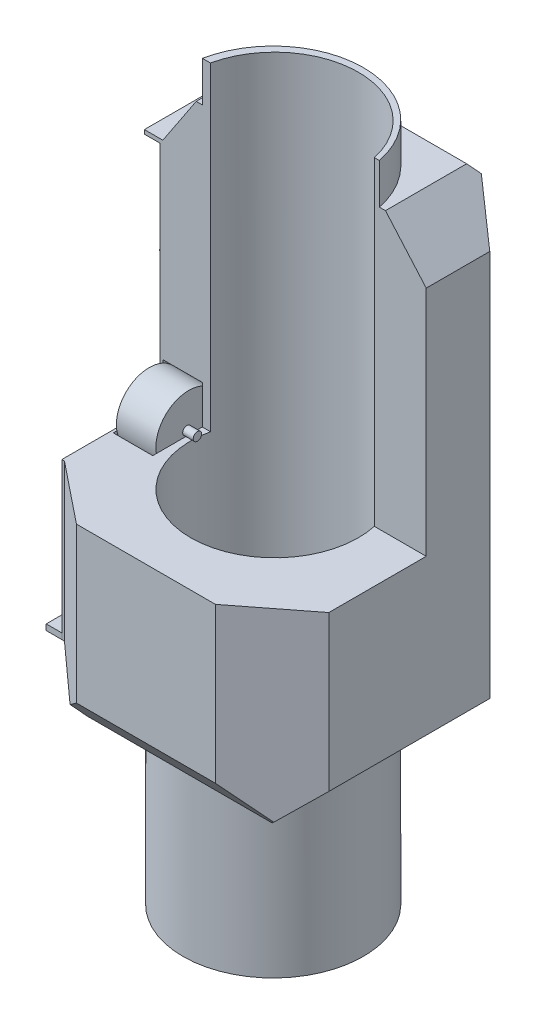
SolidWorks part; units mm, degrees
ref_plane "Front Plane" through (0, 0, 0) normal (0, 0, 1) x (1, 0, 0)
ref_plane "Top Plane" through (0, 0, 0) normal (0, 1, 0) x (1, 0, 0)
ref_plane "Right Plane" through (0, 0, 0) normal (1, 0, 0) x (0, 0, -1)
sketch "Sketch1" plane through (0, 0, 0) normal (0, 1, 0) x (1, 0, 0)
  line L1 (0, 0) -> (-100, 0)
  line L2 (0, 0) -> (0, 100)
  line L3 (0, 100) -> (-100, 100)
  line L4 (-100, 0) -> (-100, 100)
  dimension "D1" = 100
  dimension "D2" = 100
extrude "Boss-Extrude1" add sketch "Sketch1" along normal blind 180
sketch "Sketch2" plane through (0, 180, 0) normal (0, 1, 0) x (1, 0, 0)
  circle A0 centre (-51.3773, 49.0765) radius 34.2578
  point P2 (-49.1037, 52.2166)
  point P3 (-48.8771, 51.8469)
  point P4 (-51.3773, 49.0765)
extrude "Boss-Extrude2" add sketch "Sketch2" along normal mid plane 700
sketch "Sketch3" plane through (0, 0, 0) normal (1, 0, 0) x (0, 0, -1)
  line L1 (-18.5833, 361.0481) -> (133.4231, 361.0481)
  line L2 (-18.5833, 361.0481) -> (-18.5833, 643.5005)
  line L3 (-18.5833, 643.5005) -> (133.4231, 643.5005)
  line L4 (133.4231, 361.0481) -> (133.4231, 643.5005)
extrude "Cut-Extrude2" cut sketch "Sketch3" against normal blind 400
sketch "Sketch4" plane through (0, 0, 0) normal (1, 0, 0) x (0, 0, -1)
  line L0 (12.982, 0) -> (-8.9942, 25.8281)
  line L1 (-8.9942, 25.8281) -> (-18.5645, -15.2595)
  line L2 (-18.5645, -15.2595) -> (12.982, 0)
  line L3 (85.0725, -1.4481) -> (109.2376, 19.1131)
  line L4 (109.2376, 19.1131) -> (115.92, -3.2674)
  line L5 (115.92, -3.2674) -> (85.0725, -1.4481)
  line L6 (12.982, 180) -> (-8.9942, 148.5376)
  line L7 (-8.9942, 148.5376) -> (-15.4182, 193.2193)
  line L8 (-15.4182, 193.2193) -> (12.982, 180)
  line L9 (85.0725, 181.8543) -> (103.8412, 159.7959)
  line L10 (103.8412, 159.7959) -> (106.1325, 198.6474)
  line L11 (106.1325, 198.6474) -> (85.0725, 181.8543)
extrude "Cut-Extrude3" cut sketch "Sketch4" against normal blind 400
sketch "Sketch5" plane through (0, 0, 0) normal (0, 0, 1) x (1, 0, 0)
  line L0 (-85.6233, 0) -> (-106.3704, 21.4264)
  line L1 (-106.3704, 21.4264) -> (-122.2889, 3.2093)
  line L2 (-122.2889, 3.2093) -> (-93.5263, -19.8847)
  line L3 (-93.5263, -19.8847) -> (-85.6233, 0)
  line L4 (-15.695, 0) -> (0, 15.2574)
  line L5 (0, 15.2574) -> (12.1227, 15.2574)
  line L6 (12.1227, 15.2574) -> (10.5631, -19.8847)
  line L7 (10.5631, -19.8847) -> (-15.695, 0)
  line L8 (-87.1665, 180.2481) -> (-106.3704, 151.2911)
  line L9 (-106.3704, 151.2911) -> (-117.7055, 200.5011)
  line L10 (-117.7055, 200.5011) -> (-87.1665, 180.2481)
  line L11 (-15.695, 180.2481) -> (7.8338, 153.2796)
  line L12 (7.8338, 153.2796) -> (0, 193.9412)
  line L13 (0, 193.9412) -> (-15.695, 180.2481)
extrude "Cut-Extrude4" cut sketch "Sketch5" against normal blind 400
sketch "Sketch6" plane through (0, 180, 0) normal (0, 1, 0) x (1, 0, 0)
  line L1 (-112.387, 28.4004) -> (-64.2613, -10.2128)
  line L2 (-112.387, 28.4004) -> (-124.6497, -15.5119)
  line L3 (-124.6497, -15.5119) -> (-84.4064, -15.5119)
  line L4 (-64.2613, -10.2128) -> (-84.4064, -15.5119)
  line L5 (-97.0655, 135.8618) -> (-119.3755, 77.7927)
  line L6 (-97.0655, 135.8618) -> (-66.4287, 110.5752)
  line L7 (-66.4287, 110.5752) -> (-118.0433, 64.3476)
  line L8 (-119.3755, 77.7927) -> (-118.0433, 64.3476)
  line L9 (-24.6964, -21.8158) -> (11.0921, -8.9736)
  line L10 (-24.6964, -21.8158) -> (-38.5316, -11.1392)
  line L11 (-38.5316, -11.1392) -> (17.4283, 32.3938)
  line L12 (11.0921, -8.9736) -> (17.4283, 32.3938)
  line L13 (-17.4455, 140.8044) -> (35.4175, 107.2625)
  line L14 (-17.4455, 140.8044) -> (-31.7244, 103.6253)
  line L15 (-31.7244, 103.6253) -> (9.3055, 72.9964)
  line L16 (35.4175, 107.2625) -> (9.3055, 72.9964)
  point P4 (-17.4455, 140.8044)
  point P5 (-30.2763, 114.984)
  point P6 (35.4175, 107.2625)
  point P19 (-30.6265, 106.484)
  point P20 (-11.2095, 88.3109)
extrude "Cut-Extrude5" cut sketch "Sketch6" against normal blind 400
sketch "Sketch7" plane through (0, 0, 0) normal (0, 0, 1) x (1, 0, 0)
  line L1 (-146.2029, -210.0437) -> (13.9564, -210.0437)
  line L2 (-146.2029, -210.0437) -> (-146.2029, -62.6814)
  line L3 (-146.2029, -62.6814) -> (13.9564, -62.6814)
  line L4 (13.9564, -210.0437) -> (13.9564, -62.6814)
extrude "Cut-Extrude6" cut sketch "Sketch7" against normal blind 400
sketch "Sketch8" plane through (0, 0, 0) normal (0, 0, 1) x (1, 0, 0)
  line L1 (-127.1965, 251.4288) -> (20.1142, 251.4288)
  line L2 (-127.1965, 251.4288) -> (-127.1965, 413.4677)
  line L3 (-127.1965, 413.4677) -> (20.1142, 413.4677)
  line L4 (20.1142, 251.4288) -> (20.1142, 413.4677)
extrude "Cut-Extrude7" cut sketch "Sketch8" against normal blind 400
sketch "Sketch9" plane through (0, 251.4288, 0) normal (0, 1, 0) x (1, 0, 0)
  circle A0 centre (-50.809, 49.032) radius 31.8473
  point P2 (-50.6049, 49.6989)
  point P3 (-51.6378, 48.9774)
  point P4 (-50.809, 49.032)
extrude "Cut-Extrude8" cut sketch "Sketch9" against normal blind 400
sketch "Sketch10" plane through (-100, 0, 0) normal (-1, 0, 0) x (0, 0, 1)
  line L1 (-55.8114, 74.0839) -> (84.4096, 74.0839)
  line L2 (-55.8114, 74.0839) -> (-55.8114, 286.1174)
  line L3 (-55.8114, 286.1174) -> (84.4096, 286.1174)
  line L4 (84.4096, 74.0839) -> (84.4096, 286.1174)
extrude "Cut-Extrude9" cut sketch "Sketch10" against normal blind 400
sketch "Sketch11" plane through (-100, 0, 0) normal (-1, 0, 0) x (0, 0, 1)
  circle A0 centre (-50.4133, 76.2646) radius 13.6031
  point P2 (-50.4133, 76.2646)
extrude "Cut-Extrude11" cut sketch "Sketch11" against normal blind 15
sketch "Sketch12" plane through (-85, 0, 0) normal (-1, 0, 0) x (0, 0, 1)
  circle A0 centre (-50.6588, 76.2225) radius 12.4954
  point P2 (-51.6147, 75.8831)
  point P3 (-50.6588, 76.2225)
extrude "Boss-Extrude3" add sketch "Sketch12" along normal blind 15
sketch "Sketch13" plane through (-85, 0, 0) normal (1, 0, 0) x (0, 0, -1)
  circle A0 centre (49.9452, 75.9448) radius 1.5949
extrude "Boss-Extrude4" add sketch "Sketch13" along normal blind 4
sketch "Sketch14" plane through (-100, 0, 0) normal (-1, 0, 0) x (0, 0, 1)
  line L1 (-115.7243, 195.3259) -> (-14.9757, 195.3259)
  line L2 (-115.7243, 195.3259) -> (-115.7243, 305.8809)
  line L3 (-115.7243, 305.8809) -> (-14.9757, 305.8809)
  line L4 (-14.9757, 195.3259) -> (-14.9757, 305.8809)
extrude "Cut-Extrude13" cut sketch "Sketch14" against normal blind 400
sketch "Sketch15" plane through (-100, 0, 0) normal (-1, 0, 0) x (0, 0, 1)
  line L0 (-18.4618, 14.8474) -> (-80.5077, 14.8474)
  line L1 (-80.5077, 14.8474) -> (-80.5077, 160.8968)
  line L2 (-80.5077, 160.8968) -> (-55.8114, 160.8968)
  line L3 (-55.8114, 160.8968) -> (-55.8114, 74.0839)
  line L4 (-55.8114, 74.0839) -> (-18.4618, 74.0839)
  line L5 (-18.4618, 74.0839) -> (-18.4618, 14.8474)
extrude "Boss-Extrude5" add sketch "Sketch15" along normal blind 1
sketch "Sketch16" plane through (-101, 0, 0) normal (-1, 0, 0) x (0, 0, 1)
  line L1 (-51.5273, 29.9073) -> (-27.023, 29.9073)
  line L2 (-51.5273, 29.9073) -> (-51.5273, 60.3656)
  line L3 (-51.5273, 60.3656) -> (-27.023, 60.3656)
  line L4 (-27.023, 29.9073) -> (-27.023, 60.3656)
extrude "Boss-Extrude6" add sketch "Sketch16" along normal blind 5
sketch "Sketch17" plane through (-101, 0, 0) normal (-1, 0, 0) x (0, 0, 1)
  line L1 (-76.3814, 119.2079) -> (-57.7119, 119.2079)
  line L2 (-76.3814, 119.2079) -> (-76.3814, 141.6106)
  line L3 (-76.3814, 141.6106) -> (-57.7119, 141.6106)
  line L4 (-57.7119, 119.2079) -> (-57.7119, 141.6106)
extrude "Boss-Extrude7" add sketch "Sketch17" along normal blind 1
sketch "Sketch18" plane through (-102, 0, 0) normal (-1, 0, 0) x (0, 0, 1)
  line L1 (-74.0789, 127.628) -> (-69.1713, 127.628)
  line L2 (-74.0789, 127.628) -> (-74.0789, 132.7988)
  line L3 (-74.0789, 132.7988) -> (-69.1713, 132.7988)
  line L4 (-69.1713, 127.628) -> (-69.1713, 132.7988)
  line L5 (-60.3069, 127.1415) -> (-64.2884, 127.1415)
  line L6 (-60.3069, 127.1415) -> (-60.3069, 132.5929)
  line L7 (-60.3069, 132.5929) -> (-64.2884, 132.5929)
  line L8 (-64.2884, 127.1415) -> (-64.2884, 132.5929)
extrude "Boss-Extrude8" add sketch "Sketch18" along normal blind 1
sketch "Sketch19" plane through (-102, 0, 0) normal (-1, 0, 0) x (0, 0, 1)
  line L0 (-66.9765, 134.8688) -> (-73.7929, 134.8688)
  line L1 (-73.7929, 134.8688) -> (-73.7929, 134.1083)
  line L2 (-73.7929, 134.1083) -> (-74.5719, 134.1083)
  line L3 (-74.5719, 134.1083) -> (-74.5719, 140.5127)
  line L4 (-74.5719, 140.5127) -> (-73.7929, 140.5127)
  line L5 (-73.7929, 140.5127) -> (-72.166, 140.5127)
  line L6 (-66.9765, 134.8688) -> (-66.9765, 135.4972)
  line L7 (-66.9765, 135.4972) -> (-73.7929, 135.4233)
  line L8 (-73.7929, 135.4233) -> (-73.7929, 139.5456)
  line L9 (-73.7929, 139.5456) -> (-72.9212, 139.5456)
  line L10 (-72.9212, 139.5456) -> (-72.9212, 136.6931)
  line L11 (-72.166, 140.5127) -> (-72.2334, 137.4219)
  line L12 (-72.9212, 136.6931) -> (-70.7839, 136.6931)
  line L13 (-72.2334, 137.4219) -> (-71.4846, 137.4219)
  line L14 (-71.4846, 137.4219) -> (-71.4109, 140.5127)
  line L15 (-71.4109, 140.5127) -> (-69.1583, 140.5049)
  line L16 (-70.7839, 136.6931) -> (-70.7097, 139.9027)
  line L17 (-70.7097, 139.9027) -> (-70.0087, 139.9027)
  line L18 (-69.1583, 140.5049) -> (-69.1583, 137.4219)
  line L19 (-70.0087, 139.9027) -> (-70.0087, 136.6677)
  line L20 (-70.0087, 136.6677) -> (-67.49, 136.6677)
  line L21 (-69.1583, 137.4219) -> (-68.2217, 137.4219)
  line L22 (-67.49, 136.6677) -> (-67.49, 139.9027)
  line L23 (-67.49, 139.9027) -> (-66.3346, 139.9027)
  line L24 (-66.3346, 139.9027) -> (-66.3346, 136.6677)
  line L25 (-68.2217, 137.4219) -> (-68.2217, 140.5679)
  line L26 (-68.2217, 140.5679) -> (-65.4269, 140.5679)
  line L27 (-65.4269, 140.5679) -> (-65.5152, 137.4462)
  line L28 (-66.3346, 136.6677) -> (-64.0048, 136.6677)
  line L29 (-64.0048, 136.6677) -> (-64.0048, 139.9797)
  line L30 (-64.0048, 139.9797) -> (-63.0901, 139.9797)
  line L31 (-63.0901, 139.9797) -> (-63.0901, 136.6677)
  line L32 (-63.0901, 136.6677) -> (-60.6958, 136.6677)
  line L33 (-60.6958, 136.6677) -> (-60.6958, 139.9841)
  line L34 (-60.6958, 139.9841) -> (-59.6983, 139.9949)
  line L35 (-65.5152, 137.4462) -> (-64.7141, 137.4462)
  line L36 (-64.7141, 137.4462) -> (-64.7141, 140.5679)
  line L37 (-64.7141, 140.5679) -> (-62.4109, 140.5679)
  line L38 (-62.4109, 140.5679) -> (-62.4109, 137.2101)
  line L39 (-62.4109, 137.2101) -> (-61.4035, 137.2101)
  line L40 (-61.4035, 137.2101) -> (-61.4035, 140.6311)
  line L41 (-61.4035, 140.6311) -> (-58.89, 140.6311)
  line L42 (-58.89, 140.6311) -> (-58.89, 136.5955)
  line L43 (-58.89, 136.5955) -> (-59.6983, 136.5955)
  line L44 (-59.6983, 136.5955) -> (-59.6983, 139.9949)
  point P27 (-64.7141, 140.5679)
extrude "Boss-Extrude9" add sketch "Sketch19" along normal blind 1
sketch "Sketch21" plane through (-101, 0, 0) normal (-1, 0, 0) x (0, 0, 1)
  line L1 (-51.9721, 29.5069) -> (-68.2534, 29.5069)
  line L2 (-51.9721, 29.5069) -> (-51.9721, 60.2117)
  line L3 (-51.9721, 60.2117) -> (-68.2534, 60.2117)
  line L4 (-68.2534, 29.5069) -> (-68.2534, 60.2117)
extrude "Boss-Extrude10" add sketch "Sketch21" along normal blind 5
sketch "Sketch22" plane through (-102, 0, 0) normal (-1, 0, 0) x (0, 0, 1)
  line L1 (-61.0903, 132.5972) -> (-60.5286, 132.5972)
  line L2 (-61.0903, 132.5972) -> (-61.0903, 133.2011)
  line L3 (-61.0903, 133.2011) -> (-60.5286, 133.2011)
  line L4 (-60.5286, 132.5972) -> (-60.5286, 133.2011)
  line L5 (-61.425, 132.5972) -> (-61.9595, 132.5972)
  line L6 (-61.425, 132.5972) -> (-61.425, 133.2011)
  line L7 (-61.425, 133.2011) -> (-61.9595, 133.2011)
  line L8 (-61.9595, 132.5972) -> (-61.9595, 133.2011)
  line L9 (-62.3566, 132.6053) -> (-62.8933, 132.6053)
  line L10 (-62.3566, 132.6053) -> (-62.3566, 133.2011)
  line L11 (-62.3566, 133.2011) -> (-62.8933, 133.2011)
  line L12 (-62.8933, 132.6053) -> (-62.8933, 133.2011)
  line L13 (-63.2722, 132.5972) -> (-63.8273, 132.5972)
  line L14 (-63.2722, 132.5972) -> (-63.2722, 133.2011)
  line L15 (-63.2722, 133.2011) -> (-63.8273, 133.2011)
  line L16 (-63.8273, 132.5972) -> (-63.8273, 133.2011)
  line L17 (-60.5286, 127.1114) -> (-61.0903, 127.1114)
  line L18 (-60.5286, 127.1114) -> (-60.5286, 126.5079)
  line L19 (-60.5286, 126.5079) -> (-61.0903, 126.5079)
  line L20 (-61.0903, 127.1114) -> (-61.0903, 126.5079)
  line L21 (-61.425, 127.1139) -> (-61.9595, 127.1139)
  line L22 (-61.425, 127.1139) -> (-61.425, 126.5079)
  line L23 (-61.425, 126.5079) -> (-61.9595, 126.5079)
  line L24 (-61.9595, 127.1139) -> (-61.9595, 126.5079)
  line L25 (-62.3566, 127.1139) -> (-62.8685, 127.1139)
  line L26 (-62.3566, 127.1139) -> (-62.3566, 126.5079)
  line L27 (-62.3566, 126.5079) -> (-62.8685, 126.5079)
  line L28 (-62.8685, 127.1139) -> (-62.8685, 126.5079)
  line L29 (-63.2722, 127.1139) -> (-63.8273, 127.1139)
  line L30 (-63.2722, 127.1139) -> (-63.2722, 126.5079)
  line L31 (-63.2722, 126.5079) -> (-63.8273, 126.5079)
  line L32 (-63.8273, 127.1139) -> (-63.8273, 126.5079)
extrude "Boss-Extrude11" add sketch "Sketch22" along normal blind 1
sketch "Sketch23" plane through (-101, 0, 0) normal (-1, 0, 0) x (0, 0, 1)
  line L1 (-18.5378, 14.7914) -> (-79.2138, 14.7914)
  line L2 (-18.5378, 14.7914) -> (-18.5378, 17.0023)
  line L3 (-18.5378, 17.0023) -> (-79.2138, 17.0023)
  line L5 (-80.5071, 14.7914) -> (-79.2138, 14.7914)
  line L6 (-80.5071, 14.7914) -> (-80.5071, 159.3713)
  line L8 (-79.2138, 17.0023) -> (-79.2138, 159.3713)
  line L9 (-79.2138, 159.3713) -> (-55.8114, 159.3713)
  line L10 (-80.5071, 159.3713) -> (-80.5071, 160.8968)
  line L11 (-80.5071, 160.8968) -> (-55.8114, 160.8968)
  line L12 (-55.8114, 159.3713) -> (-55.8114, 160.8968)
extrude "Boss-Extrude12" add sketch "Sketch23" along normal blind 6
sketch "Sketch25" plane through (-102, 0, 0) normal (-1, 0, 0) x (0, 0, 1)
  line L1 (-62.1557, 123.1023) -> (-60.1038, 123.1023)
  line L2 (-62.1557, 123.1023) -> (-62.1557, 124.5341)
  line L3 (-62.1557, 124.5341) -> (-60.1038, 124.5341)
  line L4 (-60.1038, 123.1023) -> (-60.1038, 124.5341)
  line L5 (-66.0924, 123.264) -> (-64.2964, 123.264)
  line L6 (-66.0924, 123.264) -> (-66.0924, 124.6655)
  line L7 (-66.0924, 124.6655) -> (-64.2964, 124.6655)
  line L8 (-64.2964, 123.264) -> (-64.2964, 124.6655)
  line L9 (-67.7924, 123.3502) -> (-70.0292, 123.3502)
  line L10 (-67.7924, 123.3502) -> (-67.7924, 124.9796)
  line L11 (-67.7924, 124.9796) -> (-70.0292, 124.9796)
  line L12 (-70.0292, 123.3502) -> (-70.0292, 124.9796)
  line L13 (-65.236, 132.1422) -> (-68.336, 132.1422)
  line L14 (-65.236, 132.1422) -> (-65.236, 134.6375)
  line L15 (-65.236, 134.6375) -> (-68.336, 134.6375)
  line L16 (-68.336, 132.1422) -> (-68.336, 134.6375)
extrude "Boss-Extrude14" add sketch "Sketch25" along normal blind 1
sketch "Sketch26" plane through (-102, 0, 0) normal (-1, 0, 0) x (0, 0, 1)
  circle A0 centre (-60.1106, 120.378) radius 0.5737
  circle A1 centre (-62.6787, 120.378) radius 0.4657
  circle A2 centre (-64.7436, 120.378) radius 0.4938
  circle A3 centre (-66.8145, 120.378) radius 0.5212
  circle A4 centre (-73.1094, 124.4431) radius 1.2793
extrude "Boss-Extrude15" add sketch "Sketch26" along normal blind 3
